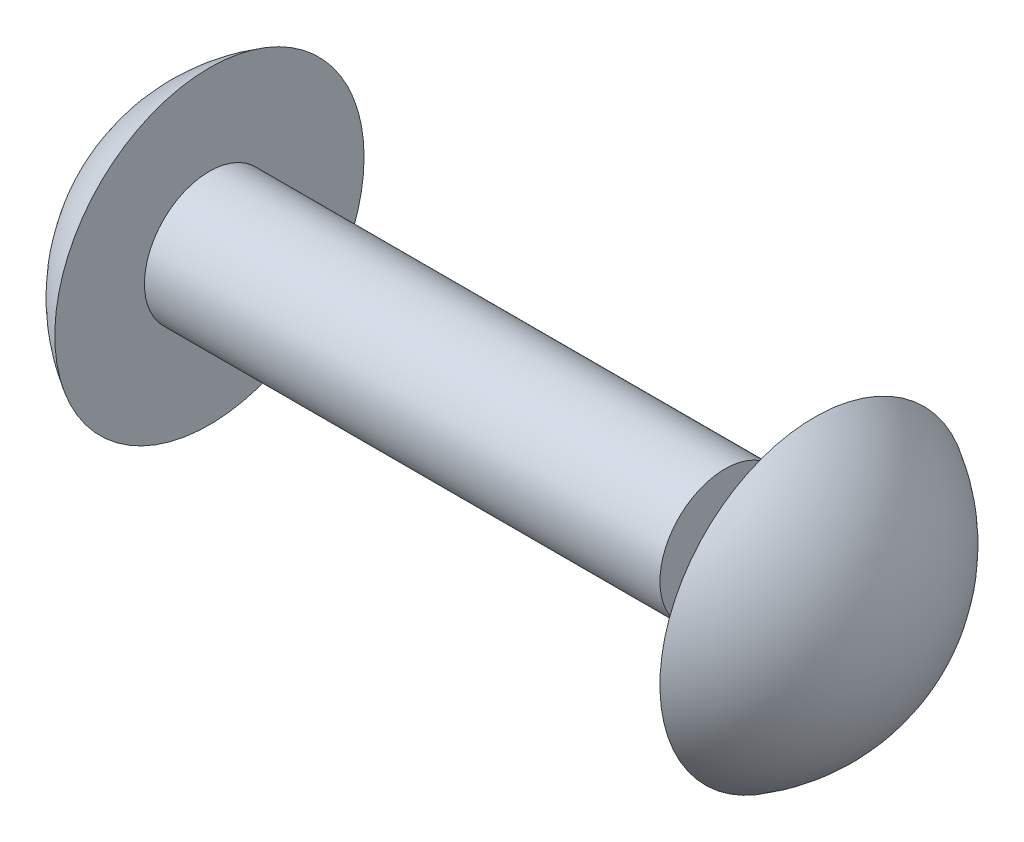
SolidWorks part; units mm, degrees
ref_plane "Front Plane" through (0, 0, 0) normal (1, 0, 0) x (0, 1, 0)
ref_plane "Top Plane" through (0, 0, 0) normal (0, 0, 1) x (0, 1, 0)
ref_plane "Right Plane" through (0, 0, 0) normal (0, 1, 0) x (-1, 0, 0)
sketch "Sketch2" plane through (0, 0, 0) normal (1, 0, 0) x (0, 1, 0)
  circle A0 centre (0, 0) radius 1.45
  dimension "D1" = 2.9
extrude "Boss-Extrude1" add sketch "Sketch2" along normal mid plane 11.5
sketch "Sketch3" plane through (0, 0, 0) normal (0, 0, 1) x (0, 1, 0)
  line L1 (1.45, 5.75) -> (-1.45, 5.75) construction
  line L2 (1.45, 5.75) -> (-1.45, 5.75) construction
  line L3 (0, 5.75) -> (0, 7.75)
  line L4 (3.45, 5.75) -> (0, 5.75)
  arc A0 (0, 7.75) -> (3.45, 5.75) centre (0, 3.7744) cw
  point P0 (0.7241, 5.6187)
  point P5 (0, 5.75)
  point P6 (0, 5.75)
  dimension "D1" = 3.45
  dimension "D2" = 2
revolve "Revolve1" add sketch "Sketch3" angle 360 about L3
ref_plane "Plane1" through (1, 0, 0) normal (1, 0, 0) x (0, 1, 0)
sketch "Sketch4" plane through (1, 0, 0) normal (1, 0, 0) x (0, 1, 0)
  line L0 (0, 0) -> (0, 0.8632) construction
pattern_circular "CirPattern3" count 2 every 180 about axis through (1, 0, 0) along (0, 0, 1) of bodies 102
